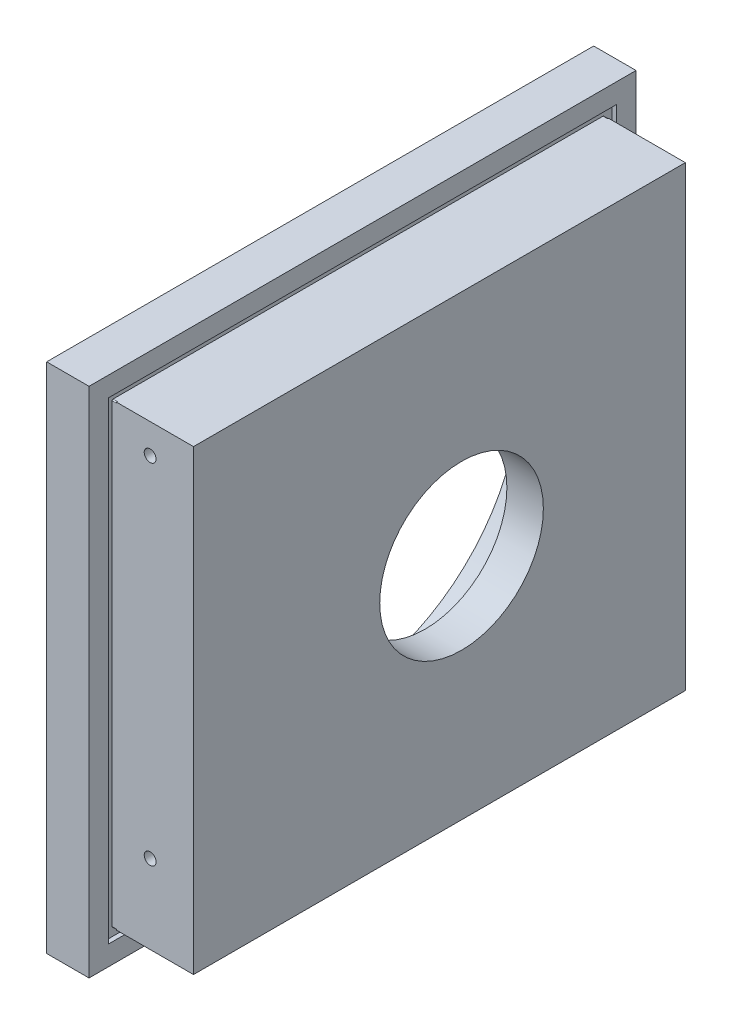
SolidWorks part; units mm, degrees
ref_plane "Front Plane" through (0, 0, 0) normal (0, 0, 1) x (1, 0, 0)
ref_plane "Top Plane" through (0, 0, 0) normal (0, 1, 0) x (1, 0, 0)
ref_plane "Right Plane" through (0, 0, 0) normal (1, 0, 0) x (0, 0, -1)
sketch "Sketch1" plane through (0, 0, 0) normal (1, 0, 0) x (0, 0, -1)
  line L1 (-150, -130) -> (150, -130)
  line L2 (-150, -130) -> (-150, 130)
  line L3 (-150, 130) -> (150, 130)
  line L4 (150, -130) -> (150, 130)
  point P5 (150, 0)
  point P6 (0, -130)
  dimension "D1" = 260
  dimension "D2" = 300
extrude "Boss-Extrude1" add sketch "Sketch1" along normal blind 60.5
sketch "Sketch2" plane through (0, 0, 0) normal (1, 0, 0) x (0, 0, -1)
  line L0 (150, 130) -> (-150, 130) construction
  line L1 (-150, 130) -> (-150, -130) construction
  circle A0 centre (0, 0) radius 90.45
  point P5 (0, 130)
  point P8 (-150, 0)
  dimension "D1" = 180.9
extrude "Cut-Extrude1" cut sketch "Sketch2" along normal blind 42
sketch "Sketch4" plane through (0, 0, 0) normal (1, 0, 0) x (0, 0, -1)
  line L0 (0, 0) -> (0, 107.825) construction
  line L1 (45.5688, 97.7226) -> (0, 0) construction
  line L2 (0, 0) -> (-45.5688, 97.7226) construction
  line L3 (-107.825, 0) -> (107.825, 0) construction
  circle A1 centre (0, 0) radius 125
  circle A8 centre (0, 0) radius 107.825 construction
  circle A9 centre (0, 107.825) radius 5
  circle A10 centre (-82.5987, 69.3086) radius 5
  circle A11 centre (82.5987, 69.3086) radius 5
  circle A12 centre (82.5987, -69.3086) radius 5
  circle A13 centre (0, -107.825) radius 5
  circle A14 centre (-82.5987, -69.3086) radius 5
  dimension "D1" = 250
  dimension "D5" = 10
  dimension "D2" = 215.65
  dimension "D3" = 25
  dimension "D4" = 25
ref_plane "Plane1" through (0, 0, 150) normal (0, 0, 1) x (1, 0, 0)
ref_plane "Plane2" through (0, -130, 0) normal (0, -1, 0) x (-1, 0, 0)
sketch "Sketch9" plane through (0, 0, 0) normal (1, 0, 0) x (0, 0, -1)
  circle A0 centre (0, 0) radius 41.51
  dimension "D1" = 83.02
extrude "Cut-Extrude9" cut sketch "Sketch9" along normal blind 306
ref_plane "Plane3" through (60.5, 0, 0) normal (1, 0, 0) x (0, 0, -1)
ref_plane "Plane4" through (0, 0, 150) normal (0, 0, 1) x (1, 0, 0)
sketch "Sketch12" plane through (0, 0, 150) normal (0, 0, 1) x (1, 0, 0)
  line L6 (21.5, -130) -> (60.5, -130)
  line L7 (21.5, -130) -> (21.5, 130)
  line L8 (21.5, 130) -> (60.5, 130)
  line L9 (60.5, -130) -> (60.5, 130)
  dimension "D1" = 39
extrude "Cut-Extrude12" cut sketch "Sketch12" against normal blind 14
ref_plane "Plane5" through (0, 0, -150) normal (0, 0, -1) x (-1, 0, 0)
sketch "Sketch13" plane through (0, 0, -150) normal (0, 0, -1) x (-1, 0, 0)
  line L8 (-21.5, -130) -> (-60.5, -130)
  line L9 (-21.5, -130) -> (-21.5, 130)
  line L10 (-21.5, 130) -> (-60.5, 130)
  line L11 (-60.5, -130) -> (-60.5, 130)
  dimension "D1" = 39
extrude "Cut-Extrude13" cut sketch "Sketch13" against normal blind 36.45
sketch "Sketch14" plane through (0, 0, 150) normal (0, 0, 1) x (1, 0, 0)
  line L0 (21.5, 130) -> (21.5, -130) construction
  line L1 (60.5, -130) -> (21.5, -130)
  line L2 (60.5, -130) -> (60.5, -116)
  line L3 (60.5, -116) -> (21.5, -116)
  line L4 (21.5, -130) -> (21.5, -116)
  dimension "D1" = 14
extrude "Cut-Extrude14" cut sketch "Sketch14" against normal through all
sketch "Sketch15" plane through (0, 0, 0) normal (1, 0, 0) x (0, 0, -1)
  line L0 (-150, -130) -> (150, -130) construction
  line L1 (150, 130) -> (127.55, 130)
  line L2 (150, 130) -> (150, -130)
  line L3 (150, -130) -> (127.55, -130)
  line L4 (127.55, 130) -> (127.55, -130)
  dimension "D1" = 22.45
extrude "Cut-Extrude15" cut sketch "Sketch15" along normal through all
sketch "Sketch16" plane through (0, 0, 150) normal (0, 0, 1) x (1, 0, 0)
  line L0 (21.5, -130) -> (0, -130) construction
  line L2 (60.5, 130) -> (21.5, 130) construction
  line L4 (21.5, 130) -> (21.5, -116) construction
  circle A0 centre (38.5, 101) radius 3
  circle A1 centre (38.5, -76) radius 3
  dimension "D1" = 54
  dimension "D4" = 6
  dimension "D5" = 6
  dimension "D2" = 17
  dimension "D3" = 29
hole_wizard "Ø6.0mm Dowel Hole1" positions "Sketch17" profile "Sketch18" hole size "Ø6.0" standard "ISO"
sketch "Sketch17" plane through (0, 0, 136) normal (0, 0, 1) x (1, 0, 0)
  point P0 (38.5, 101)
  point P3 (38.5, -76)
sketch "Sketch18" plane through (38.5, 101, 136) normal (1, 0, 0) x (0, -1, 0)
  line L0 (0, 0) -> (0, 31.8026)
  line L1 (0, 31.8026) -> (3, 30)
  line L2 (3, 30) -> (3, 0)
  line L5 (3, 0) -> (0, 0)
  line L10 (0, 31.8026) -> (-3, 30) construction
  line L11 (0, -6.35) -> (0, 107.95) construction
  dimension "Hole Dia." = 6
  dimension "Hole Depth" = 30
  dimension "Drill Angle" = 118
sketch "Sketch19" plane through (0, 0, -150) normal (0, 0, -1) x (-1, 0, 0)
  circle A0 centre (-38.5, 101) radius 3
  circle A1 centre (-38.5, -76) radius 3
  dimension "D1" = 6
  dimension "D2" = 6
hole_wizard "Ø6.0mm Dowel Hole2" positions "Sketch20" profile "Sketch21" hole size "Ø6.0" standard "ISO"
sketch "Sketch20" plane through (0, 0, -113.55) normal (0, 0, -1) x (-1, 0, 0)
  point P0 (-38.5, 101)
  point P3 (-38.5, -76)
sketch "Sketch21" plane through (38.5, 101, -113.55) normal (1, 0, 0) x (0, 1, 0)
  line L0 (0, 0) -> (0, 31.8026)
  line L1 (0, 31.8026) -> (3, 30)
  line L2 (3, 30) -> (3, 0)
  line L5 (3, 0) -> (0, 0)
  line L10 (0, 31.8026) -> (-3, 30) construction
  line L11 (0, -6.35) -> (0, 107.95) construction
  dimension "Hole Dia." = 6
  dimension "Hole Depth" = 30
  dimension "Drill Angle" = 118
sketch "Sketch22" plane through (0, -130, 0) normal (0, -1, 0) x (-1, 0, 0)
  line L0 (0, -150) -> (0, 127.55) construction
  line L2 (-21.5, -150) -> (0, -150) construction
  line L4 (-21.5, 127.55) -> (0, 127.55) construction
  circle A0 centre (-40, -120) radius 3
  circle A1 centre (-40, 97.55) radius 3
  dimension "D4" = 6
  dimension "D5" = 6
  dimension "D1" = 40
  dimension "D2" = 30
  dimension "D3" = 30
hole_wizard "Ø6.0mm Dowel Hole3" positions "Sketch23" profile "Sketch24" hole size "Ø6.0" standard "ISO"
sketch "Sketch23" plane through (0, -116, 0) normal (0, -1, 0) x (-1, 0, 0)
  point P0 (-40, -120)
  point P3 (-40, 97.55)
sketch "Sketch24" plane through (40, -116, 120) normal (1, 0, 0) x (0, 0, -1)
  line L0 (0, 0) -> (0, 16.8026)
  line L1 (0, 16.8026) -> (3, 15)
  line L2 (3, 15) -> (3, 0)
  line L5 (3, 0) -> (0, 0)
  line L10 (0, 16.8026) -> (-3, 15) construction
  line L11 (0, -6.35) -> (0, 107.95) construction
  dimension "Hole Dia." = 6
  dimension "Hole Depth" = 15
  dimension "Drill Angle" = 118
sketch "Sketch25" plane through (0, 0, -150) normal (0, 0, -1) x (-1, 0, 0)
  line L0 (-21.5, 130) -> (-21.5, -130) construction
  line L1 (-60.5, 130) -> (-21.5, 130)
  line L2 (-60.5, 130) -> (-60.5, 116)
  line L3 (-60.5, 116) -> (-21.5, 116)
  line L4 (-21.5, 130) -> (-21.5, 116)
  dimension "D1" = 14
extrude "Cut-Extrude16" cut sketch "Sketch25" against normal through all
ref_plane "Plane6" through (21.5, 0, 0) normal (1, 0, 0) x (0, 0, -1)
sketch "Sketch26" plane through (21.5, 0, 0) normal (1, 0, 0) x (0, 0, -1)
  line L1 (-135.5, 116) -> (113.05, 116)
  line L2 (-136, 115.5) -> (-136, -115.5)
  line L3 (-135.5, -116) -> (113.05, -116)
  line L4 (113.55, 115.5) -> (113.55, -115.5)
  line L5 (-140, 120) -> (117.55, 120)
  line L6 (-140, 120) -> (-140, -120)
  line L7 (-140, -120) -> (117.55, -120)
  line L8 (117.55, 120) -> (117.55, -120)
  arc A0 (-135.5, 116) -> (-136, 115.5) centre (-135.5, 115.5) ccw
  arc A1 (113.05, 116) -> (113.55, 115.5) centre (113.05, 115.5) cw
  arc A2 (113.05, -116) -> (113.55, -115.5) centre (113.05, -115.5) ccw
  arc A3 (-136, -115.5) -> (-135.5, -116) centre (-135.5, -115.5) ccw
  point P12 (-136, 116)
  point P17 (113.55, -116)
  dimension "D5" = 0.5
  dimension "D1" = 4
  dimension "D2" = 4
  dimension "D3" = 4
  dimension "D4" = 4
extrude "Cut-Extrude18" cut sketch "Sketch26" against normal blind 2.3
hole_wizard "Ø6.0mm Dowel Hole4" positions "Sketch27" profile "Sketch28" hole size "Ø6.0" standard "ISO"
sketch "Sketch27" plane through (0, 0, 0) normal (-1, 0, 0) x (0, 0, 1)
  point P0 (0, 107.825)
  point P3 (82.5987, 69.3086)
  point P6 (82.5987, -69.3086)
  point P9 (0, -107.825)
  point P12 (-82.5987, -69.3086)
  point P15 (-82.5987, 69.3086)
sketch "Sketch28" plane through (0, 107.825, 0) normal (0, 1, 0) x (0, 0, 1)
  line L0 (0, 0) -> (0, 16.8026)
  line L1 (0, 16.8026) -> (3, 15)
  line L2 (3, 15) -> (3, 0)
  line L5 (3, 0) -> (0, 0)
  line L10 (0, 16.8026) -> (-3, 15) construction
  line L11 (0, -6.35) -> (0, 107.95) construction
  dimension "Hole Dia." = 6
  dimension "Hole Depth" = 15
  dimension "Drill Angle" = 118
sketch "Sketch31" plane through (0, 0, 0) normal (1, 0, 0) x (0, 0, -1)
  circle A0 centre (0, 0) radius 100
  dimension "D1" = 200
sketch "Sketch32" plane through (0, -130, 0) normal (0, -1, 0) x (-1, 0, 0)
  line L0 (0, -150) -> (0, 127.55) construction
  line L2 (-21.5, 127.55) -> (0, 127.55) construction
  circle A0 centre (-9, -9.45) radius 2.25
  dimension "D1" = 4.5
  dimension "D2" = 9
  dimension "D3" = 137
extrude "Cut-Extrude19" cut sketch "Sketch32" against normal blind 57
sketch "Sketch33" plane through (0, 0, 0) normal (1, 0, 0) x (0, 0, -1)
  circle A0 centre (0, 0) radius 91.95
  circle A1 centre (0, 0) radius 95.95
  circle A2 centre (0, 0) radius 90.45 construction
  dimension "D1" = 4
  dimension "D2" = 1.5
extrude "Cut-Extrude21" cut sketch "Sketch33" along normal blind 2.3
